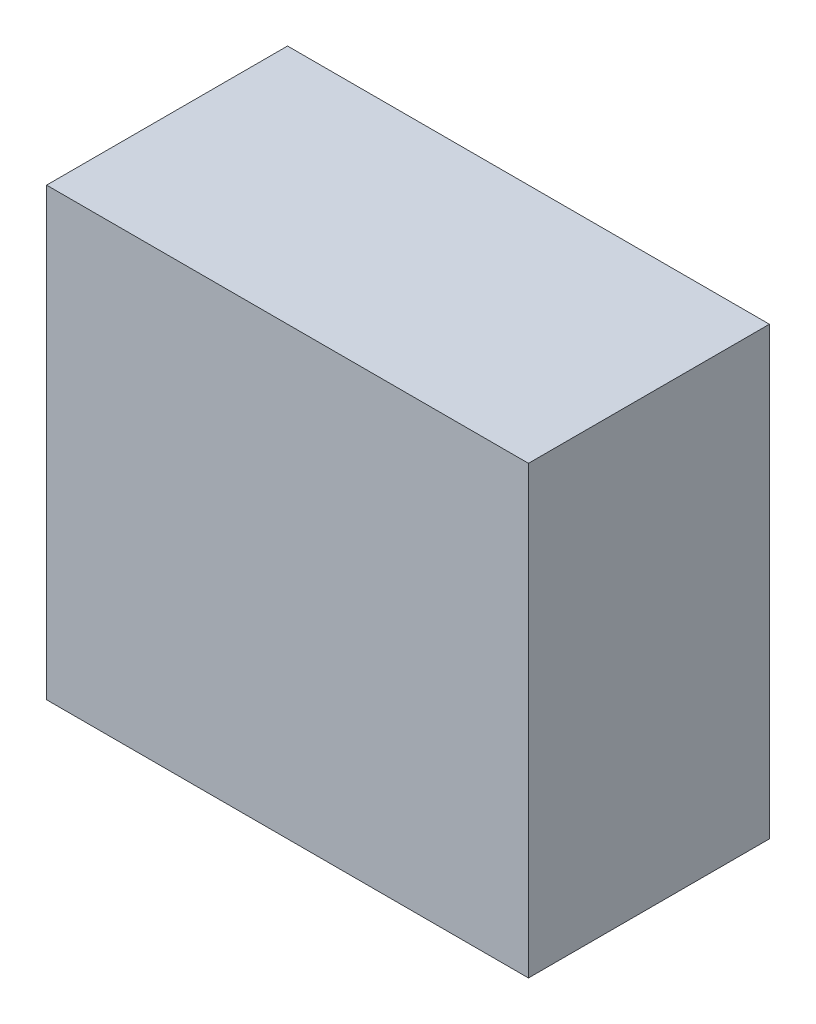
SolidWorks part; units mm, degrees
ref_plane "Plan de face" through (0, 0, 0) normal (0, 0, 1) x (1, 0, 0)
ref_plane "Plan de dessus" through (0, 0, 0) normal (0, 1, 0) x (1, 0, 0)
ref_plane "Plan de droite" through (0, 0, 0) normal (1, 0, 0) x (0, 0, -1)
sketch "Esquisse1" plane through (0, 0, 0) normal (0, 0, 1) x (1, 0, 0)
  line L1 (0, 0) -> (20, 0)
  line L2 (0, 0) -> (0, 18.5)
  line L3 (0, 18.5) -> (20, 18.5)
  line L4 (20, 0) -> (20, 18.5)
  dimension "D1" = 18.5
  dimension "D2" = 20
extrude "Boss.-Extru.1" add sketch "Esquisse1" along normal blind 10
